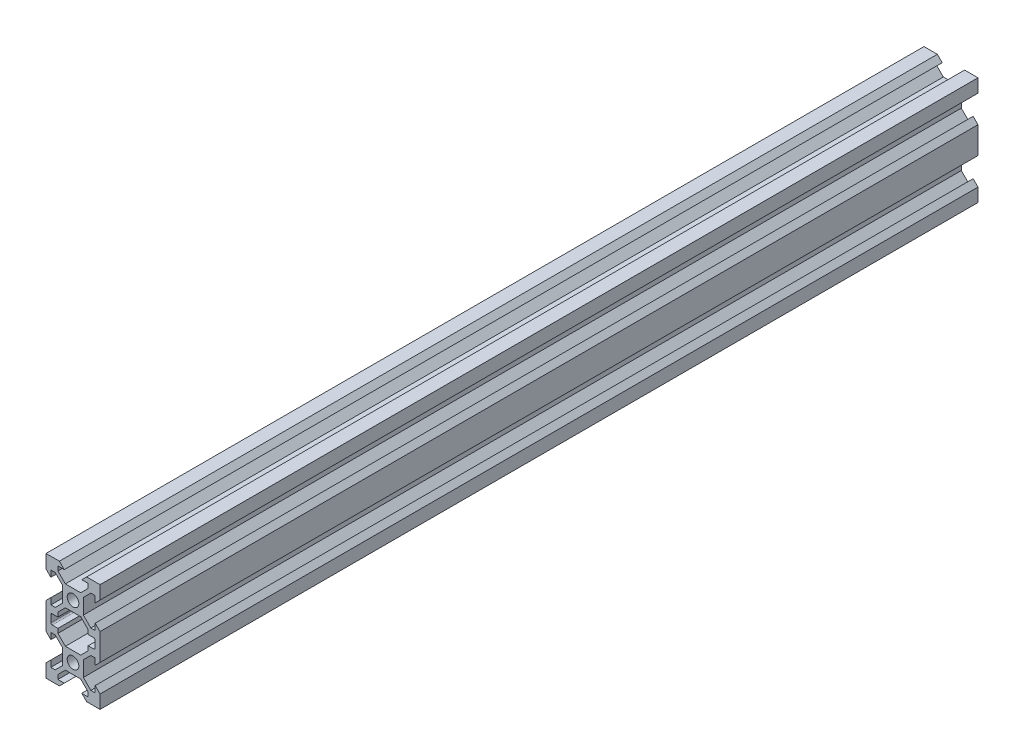
SolidWorks part; units mm, degrees
ref_plane "Alzado" through (0, 0, 0) normal (0, 0, 1) x (1, 0, 0)
ref_plane "Planta" through (0, 0, 0) normal (0, 1, 0) x (1, 0, 0)
ref_plane "Vista lateral" through (0, 0, 0) normal (1, 0, 0) x (0, 0, -1)
sketch "Croquis1" plane through (0, 0, 0) normal (0, 0, 1) x (1, 0, 0)
  line L0 (0, 0) -> (0, -20) construction
  line L2 (0, 0) -> (0, -0.5674)
  line L5 (6.175, -7.1649) -> (6.175, -12.8351)
  line L6 (7.1649, -13.825) -> (12.8351, -13.825)
  line L7 (13.825, -7.1649) -> (13.825, -12.8351)
  line L8 (7.1649, -6.175) -> (12.8351, -6.175)
  line L9 (6.175, -13.825) -> (13.825, -13.825) construction
  line L10 (13.825, -6.175) -> (13.825, -13.825) construction
  line L12 (10, -10) -> (32.1172, -10) construction
  line L13 (13.25, -18.2) -> (15.05, -20)
  line L14 (20, -20) -> (15.6, -20)
  line L15 (20, -20) -> (20, -15.6)
  line L16 (18.2, -15.6) -> (16.5899, -15.6)
  line L32 (15.6, -18.2) -> (15.6, -16.5899)
  line L33 (10, -10) -> (10, -23.2493) construction
  line L34 (4.4, -18.2) -> (4.4, -16.5899)
  line L35 (7.1649, -13.825) -> (4.4, -16.5899)
  line L36 (15.6, -18.2) -> (13.25, -18.2)
  line L38 (15.6, -20) -> (15.05, -20)
  line L40 (15.05, -20) -> (20, -20)
  line L41 (0, -20) -> (20, -20) construction
  line L42 (6.175, -12.8351) -> (3.4101, -15.6)
  line L43 (18.2, -13.25) -> (20, -15.05)
  line L44 (20, -20) -> (18.2, -20)
  line L45 (20, -20) -> (20, -15.05)
  line L48 (20, -15.05) -> (20, -20)
  line L49 (20, 0) -> (20, -20) construction
  line L50 (18.2, -15.6) -> (18.2, -13.25)
  line L51 (12.8351, -13.825) -> (15.6, -16.5899)
  line L52 (13.825, -12.8351) -> (16.5899, -15.6)
  line L53 (1.8, -15.6) -> (3.4101, -15.6)
  line L54 (1.8, -15.6) -> (1.8, -13.25)
  line L55 (1.8, -13.25) -> (0, -15.05)
  line L56 (0, 0) -> (20, 0) construction
  line L57 (0, -20) -> (0, -15.6)
  line L58 (0, -15.6) -> (0, -15.05)
  line L59 (0, -20) -> (4.4, -20)
  line L60 (0, -20) -> (4.95, -20)
  line L61 (6.75, -18.2) -> (4.95, -20)
  line L62 (4.4, -18.2) -> (6.75, -18.2)
  line L63 (1.8, -4.4) -> (3.4101, -4.4)
  line L64 (6.175, -7.1649) -> (3.4101, -4.4)
  line L65 (7.1649, -6.175) -> (4.4, -3.4101)
  line L66 (4.4, -1.8) -> (4.4, -3.4101)
  line L71 (0, 0) -> (0, -4.4)
  line L72 (0, 0) -> (0, -4.95)
  line L73 (1.8, -6.75) -> (0, -4.95)
  line L74 (1.8, -4.4) -> (1.8, -6.75)
  line L75 (15.6, -1.8) -> (15.6, -3.4101)
  line L76 (12.8351, -6.175) -> (15.6, -3.4101)
  line L77 (13.825, -7.1649) -> (16.5899, -4.4)
  line L78 (18.2, -4.4) -> (16.5899, -4.4)
  line L79 (18.2, -4.4) -> (18.2, -6.75)
  line L80 (18.2, -6.75) -> (20, -4.95)
  line L81 (20, 0) -> (20, -4.4)
  line L82 (20, -4.4) -> (20, -4.95)
  line L87 (6.175, -6.175) -> (13.825, -6.175) construction
  line L88 (6.175, -6.175) -> (6.175, -13.825) construction
  line L89 (0, 20) -> (0, 19.4326)
  line L90 (6.175, 12.8351) -> (6.175, 7.1649)
  line L91 (7.1649, 6.175) -> (12.8351, 6.175)
  line L92 (13.825, 12.8351) -> (13.825, 7.1649)
  line L93 (7.1649, 13.825) -> (12.8351, 13.825)
  line L96 (20, 0) -> (20, 4.4)
  line L97 (18.2, 4.4) -> (16.5899, 4.4)
  line L98 (15.6, 1.8) -> (15.6, 3.4101)
  line L99 (4.4, 1.8) -> (4.4, 3.4101)
  line L100 (7.1649, 6.175) -> (4.4, 3.4101)
  line L104 (6.175, 7.1649) -> (3.4101, 4.4)
  line L105 (18.2, 6.75) -> (20, 4.95)
  line L107 (20, 0) -> (20, 4.95)
  line L108 (20, 4.95) -> (20, 0)
  line L109 (18.2, 4.4) -> (18.2, 6.75)
  line L110 (12.8351, 6.175) -> (15.6, 3.4101)
  line L111 (13.825, 7.1649) -> (16.5899, 4.4)
  line L112 (1.8, 4.4) -> (3.4101, 4.4)
  line L113 (1.8, 4.4) -> (1.8, 6.75)
  line L114 (1.8, 6.75) -> (0, 4.95)
  line L115 (0, 0) -> (0, 4.4)
  line L116 (0, 4.4) -> (0, 4.95)
  line L121 (1.8, 15.6) -> (3.4101, 15.6)
  line L122 (6.175, 12.8351) -> (3.4101, 15.6)
  line L123 (7.1649, 13.825) -> (4.4, 16.5899)
  line L124 (4.4, 18.2) -> (4.4, 16.5899)
  line L125 (4.4, 18.2) -> (6.75, 18.2)
  line L126 (6.75, 18.2) -> (4.95, 20)
  line L127 (0, 20) -> (4.4, 20)
  line L128 (4.4, 20) -> (4.95, 20)
  line L129 (0, 20) -> (0, 15.6)
  line L130 (0, 20) -> (0, 15.05)
  line L131 (1.8, 13.25) -> (0, 15.05)
  line L132 (1.8, 15.6) -> (1.8, 13.25)
  line L133 (15.6, 18.2) -> (15.6, 16.5899)
  line L134 (12.8351, 13.825) -> (15.6, 16.5899)
  line L135 (13.825, 12.8351) -> (16.5899, 15.6)
  line L136 (18.2, 15.6) -> (16.5899, 15.6)
  line L137 (18.2, 15.6) -> (18.2, 13.25)
  line L138 (18.2, 13.25) -> (20, 15.05)
  line L139 (20, 20) -> (20, 15.6)
  line L140 (20, 15.6) -> (20, 15.05)
  line L141 (20, 20) -> (15.6, 20)
  line L142 (20, 20) -> (15.05, 20)
  line L143 (13.25, 18.2) -> (15.05, 20)
  line L144 (15.6, 18.2) -> (13.25, 18.2)
  line L146 (4.4, 1.8) -> (2.3, 1.8)
  line L147 (10, 10) -> (10, -3.2493) construction
  line L148 (10, 10) -> (32.1172, 10) construction
  line L150 (4.4, -1.8) -> (2.3, -1.8)
  line L151 (1.8, 1.3) -> (1.8, -1.3)
  line L152 (15.6, -1.8) -> (17.7, -1.8)
  line L154 (15.6, 1.8) -> (17.7, 1.8)
  line L155 (18.2, -1.3) -> (18.2, 1.3)
  line L156 (4.4, 1.8) -> (6.75, 1.8) [skipped]
  line L157 (6.75, 1.8) -> (4.95, 0) [skipped]
  line L158 (6.75, -1.8) -> (4.95, 0) [skipped]
  line L159 (4.4, -1.8) -> (6.75, -1.8) [skipped]
  line L160 (15.6, -1.8) -> (13.25, -1.8) [skipped]
  line L161 (13.25, -1.8) -> (15.05, 0) [skipped]
  line L162 (13.25, 1.8) -> (15.05, 0) [skipped]
  line L163 (15.6, 1.8) -> (13.25, 1.8) [skipped]
  line L164 (15.6, 0) -> (15.05, 0) [skipped]
  line L165 (4.4, 0) -> (4.95, 0) [skipped]
  line L166 (20, 0) -> (18.2, 0) [skipped]
  line L167 (18.2, 0) -> (20, 0) [skipped]
  line L168 (20, 0) -> (18.2, 0) [skipped]
  line L169 (20, 0) -> (18.2, 0) [skipped]
  line L170 (20, 0) -> (18.2, 0) [skipped]
  line L171 (0, 0) -> (1.8, 0) [skipped]
  line L172 (0, 0) -> (1.8, 0) [skipped]
  line L173 (0, 0) -> (1.8, 0) [skipped]
  circle A0 centre (10, -10) radius 2.15
  circle A1 centre (10, 10) radius 2.15
  arc A2 (17.7, 1.8) -> (18.2, 1.3) centre (17.7, 1.3) cw
  arc A3 (17.7, -1.8) -> (18.2, -1.3) centre (17.7, -1.3) ccw
  arc A4 (2.3, -1.8) -> (1.8, -1.3) centre (2.3, -1.3) cw
  arc A5 (2.3, 1.8) -> (1.8, 1.3) centre (2.3, 1.3) ccw
  point P69 (10, -10)
  point P128 (10, 10)
  dimension "D3" = 4.3
  dimension "D5" = 0.5
  dimension "D2" = 4
  dimension "D4" = 2
  dimension "D11" = 4.4
  dimension "D15" = 4.4
  dimension "D16" = 6.75
extrude "Saliente-Extruir1" add sketch "Croquis1" along normal blind 325 contours L144 L133 L134 L93 L123 L124 L125 L126 L128 L127 L89 L129 L130 L131 L132 L121 L122 L90 L104 L112 L113 L114 L116 L115 L2 L71 L72 L73 L74 L63 L64 L5 L42 L53 L54 L55 L58 L57 L59 L60 L61 L62 L34 L35 L6 L51 L32 L36 L13 L38 L40
